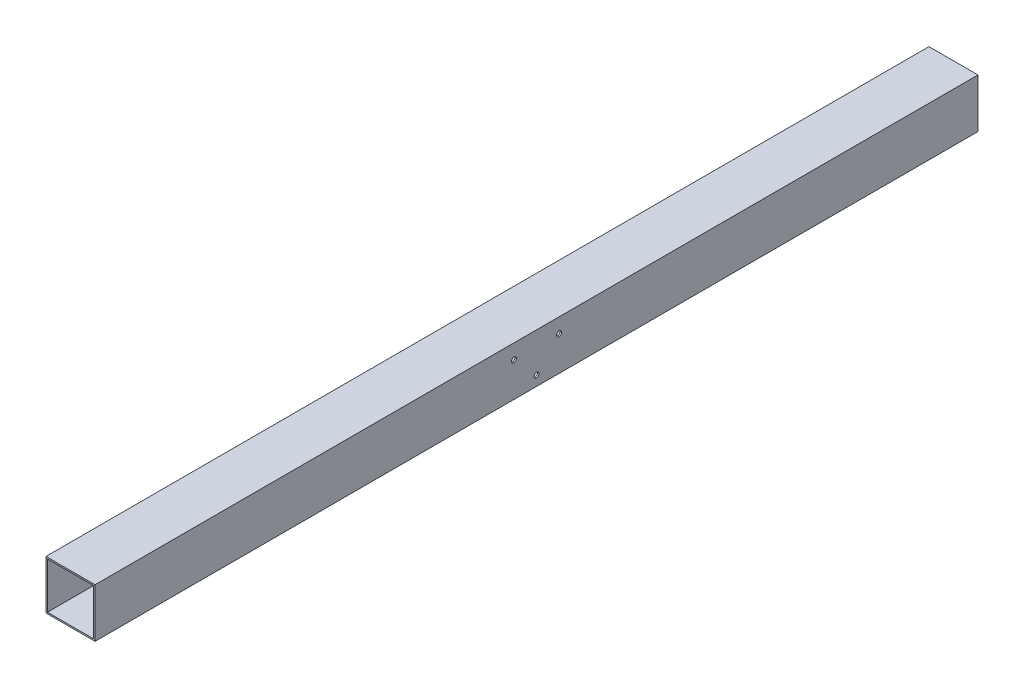
SolidWorks part; units mm, degrees
material "6061 Alloy"
ref_plane "Front Plane" through (0, 0, 0) normal (0, 0, 1) x (1, 0, 0)
ref_plane "Top Plane" through (0, 0, 0) normal (0, 1, 0) x (1, 0, 0)
ref_plane "Right Plane" through (0, 0, 0) normal (1, 0, 0) x (0, 0, -1)
sketch "Sketch1" plane through (0, 0, 0) normal (0, 0, 1) x (1, 0, 0)
  line L1 (-23.5, 23.5) -> (23.5, 23.5)
  line L2 (-23.5, 23.5) -> (-23.5, -23.5)
  line L3 (-23.5, -23.5) -> (23.5, -23.5)
  line L4 (23.5, 23.5) -> (23.5, -23.5)
  line L5 (-23.5, 23.5) -> (23.5, -23.5) construction
  line L6 (-23.5, -23.5) -> (23.5, 23.5) construction
  line L7 (-25, 25) -> (25, 25)
  line L8 (-25, 25) -> (-25, -25)
  line L9 (-25, -25) -> (25, -25)
  line L10 (25, 25) -> (25, -25)
  line L11 (-25, 25) -> (25, -25) construction
  line L12 (-25, -25) -> (25, 25) construction
  point P0 (0, 0)
  point P6 (0, 0)
  dimension "D1" = 50
  dimension "D2" = 47
  dimension "D3" = 50
  dimension "D4" = 47
extrude "Boss-Extrude1" add sketch "Sketch1" along normal blind 900
sketch "Sketch2" plane through (25, 0, 0) normal (1, 0, 0) x (0, 0, -1)
  line L0 (-900, -25) -> (0, -25) construction
  line L1 (-450, -25) -> (-450, 25) construction
  line L2 (-900, 25) -> (0, 25) construction
  line L3 (0, -25) -> (0, 25) construction
  circle A0 centre (-450, -15) radius 2.5
  circle A1 centre (-427, 10) radius 2.5
  circle A2 centre (-473, 10) radius 2.5
  point P0 (-450, -25)
  dimension "D4" = 5
  dimension "D1" = 10
  dimension "D2" = 25
  dimension "D3" = 23
  dimension "D5" = 450
extrude "Cut-Extrude1" cut sketch "Sketch2" against normal blind 59
sketch "Sketch5" plane through (25, 0, 0) normal (1, 0, 0) x (0, 0, -1)
  line L0 (-900, -25) -> (0, -25) construction
  line L1 (-900, 25) -> (0, 25) construction
  line L2 (-900, -25) -> (-900, 25) construction
  line L3 (-849.5, 25) -> (-849.5, -25) construction
  circle A0 centre (-882.5, 11) radius 3
  circle A2 centre (-882.5, -11) radius 3
  circle A3 centre (-816.5, -11) radius 3
  circle A4 centre (-816.5, 11) radius 3
  dimension "D4" = 6
  dimension "D6" = 6
  dimension "D1" = 33
  dimension "D2" = 14
  dimension "D3" = 14
  dimension "D7" = 17.5
ref_plane "Plane1" through (0, 0, 450) normal (0, 0, 1) x (1, 0, 0)
sketch "Sketch6" plane through (0, 25, 0) normal (0, 1, 0) x (1, 0, 0)
  line L0 (0, -694.2275) -> (0, -739.8525) construction
  line L2 (-27.5, -450) -> (27.5, -450) construction
  circle A0 centre (0, -694.2275) radius 3.125
  circle A1 centre (0, -739.8525) radius 3.125
  circle A2 centre (0, -717.04) radius 5
  point P8 (0, -717.04)
  dimension "D1" = 6.25
  dimension "D2" = 6.25
  dimension "D5" = 10
  dimension "D3" = 45.625
  dimension "D4" = 267.04
